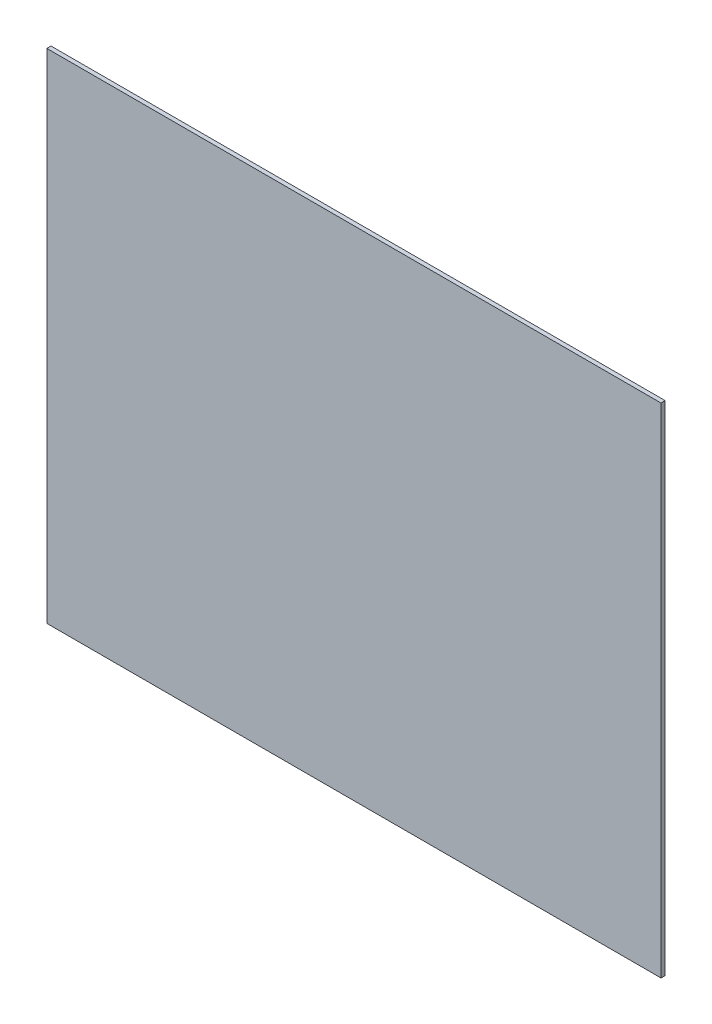
SolidWorks part; units mm, degrees
ref_plane "Front Plane" through (0, 0, 0) normal (0, 0, 1) x (1, 0, 0)
ref_plane "Top Plane" through (0, 0, 0) normal (0, 1, 0) x (1, 0, 0)
ref_plane "Right Plane" through (0, 0, 0) normal (1, 0, 0) x (0, 0, -1)
sketch "Sketch1" plane through (0, 0, 0) normal (0, 0, 1) x (1, 0, 0)
  line L1 (-234.95, -190.5) -> (234.95, -190.5)
  line L2 (-234.95, -190.5) -> (-234.95, 190.5)
  line L3 (-234.95, 190.5) -> (234.95, 190.5)
  line L4 (234.95, -190.5) -> (234.95, 190.5)
  line L5 (-234.95, -190.5) -> (234.95, 190.5) construction
  line L6 (-234.95, 190.5) -> (234.95, -190.5) construction
  point P0 (0, 0)
  dimension "D1" = 469.9
  dimension "D2" = 381
extrude "Boss-Extrude1" add sketch "Sketch1" along normal blind 3.175
